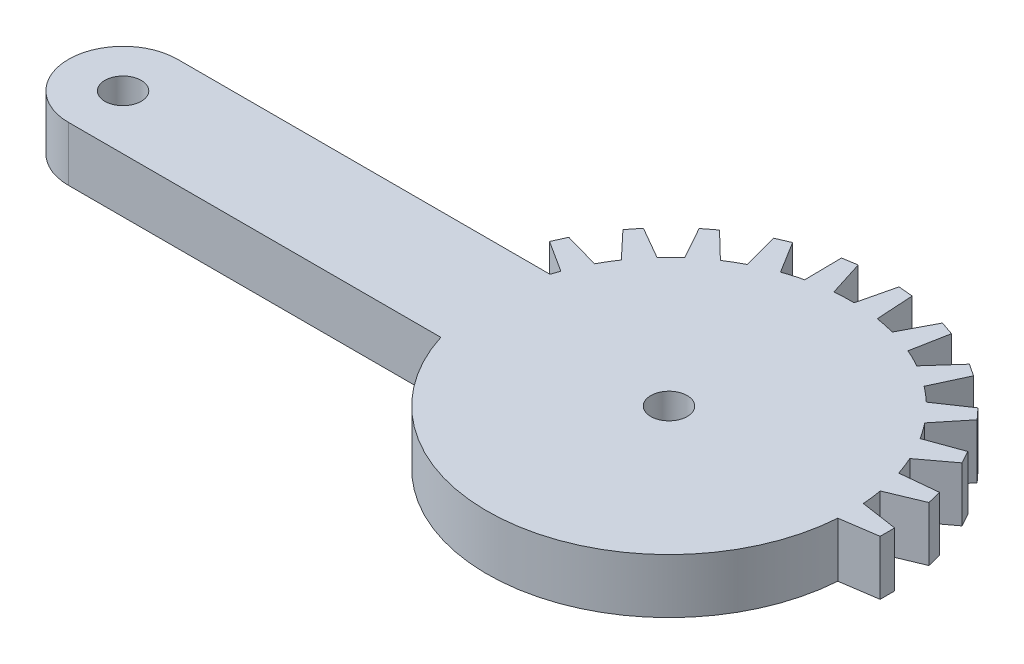
SolidWorks part; units mm, degrees
material "Oak"
ref_plane "Front" through (0, 0, 0) normal (0, 0, 1) x (1, 0, 0)
ref_plane "Top" through (0, 0, 0) normal (0, 1, 0) x (1, 0, 0)
ref_plane "Right" through (0, 0, 0) normal (1, 0, 0) x (0, 0, -1)
sketch "Sketch1" plane through (0, 0, 0) normal (0, 1, 0) x (1, 0, 0)
  line L0 (-177.6425, 0) -> (70.7426, 0) construction
  line L1 (-150, 15) -> (-47.697, 15)
  line L2 (-150, -15) -> (-47.697, -15)
  arc A0 (-47.697, -15) -> (-47.697, 15) centre (0, 0) ccw
  arc A1 (-150, 15) -> (-150, -15) centre (-150, 0) ccw
  dimension "D1" = 100
  dimension "D3" = 150
  dimension "D2" = 15
extrude "Boss-Extrude1" add sketch "Sketch1" along normal blind 15
sketch "Sketch2" plane through (0, 15, 0) normal (0, 1, 0) x (1, 0, 0)
  line L0 (88.337, 0) -> (60, 0) construction
  line L1 (49.8773, 3.5) -> (60, 2)
  line L2 (60, 2) -> (60, -2)
  line L4 (50, 0) -> (49.8773, 3.5)
  line L5 (50, 0) -> (49.8773, -3.5)
  line L6 (49.8773, -3.5) -> (60, -2)
  line L7 (50, 0) -> (-74.3015, 0) construction
  line L8 (-47.697, 15) -> (0, 0) construction
  arc A0 (-47.697, -15) -> (-47.697, 15) centre (0, 0) ccw construction
  arc A1 (49.8773, -3.5) -> (-47.697, 15) centre (0, 0) ccw
  dimension "D1" = 4
  dimension "D2" = 10
  dimension "D3" = 3.5
extrude "Boss-Extrude2" add sketch "Sketch2" against normal up to surface (15 mm away) contours L6 L2 L1 L4 L5 up to face at (-78.1742, 0, 0)
pattern_circular "CirPattern2" count 13 over 170 about axis through (0, 0, 0) along (0, 1, 0) of "Boss-Extrude2"
hole_wizard "Ø1.0mm Dowel Hole1" positions "Sketch4" profile "Sketch3" hole size "Ø1.0" standard "ANSI Metric" end condition through all
sketch "Sketch4" plane through (0, 15, 0) normal (0, 1, 0) x (1, 0, 0)
  arc A0 (-150, 15) -> (-150, -15) centre (-150, 0) ccw construction
  point P0 (-150, 0)
  point P2 (0, 0)
  dimension "D1" = 0
sketch "Sketch3" plane through (-150, 15, 0) normal (1, 0, 0) x (0, 0, 1)
  line L0 (0, 0) -> (0, 15)
  line L1 (0, 15) -> (5, 15)
  line L2 (5, 15) -> (5, 0)
  line L5 (5, 0) -> (0, 0)
  line L11 (0, -6.35) -> (0, 107.95) construction
  dimension "Thru Hole Dia." = 10
  dimension "Thru Hole Depth" = 15
scale "Escala1" scale about centroid uniform scaling yes scale factor 0.2
